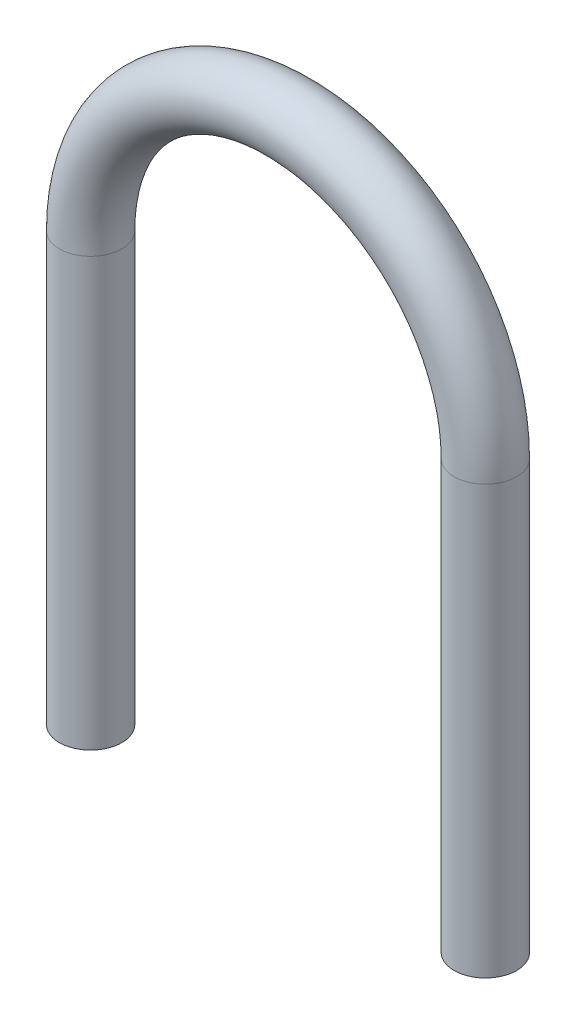
SolidWorks part; units mm, degrees
ref_plane "Front Plane" through (0, 0, 0) normal (0, 0, 1) x (1, 0, 0)
ref_plane "Top Plane" through (0, 0, 0) normal (0, 1, 0) x (1, 0, 0)
ref_plane "Right Plane" through (0, 0, 0) normal (1, 0, 0) x (0, 0, -1)
sketch "Sketch1" plane through (0, 0, 0) normal (0, 0, 1) x (1, 0, 0)
  line L0 (2, 0) -> (2, 12) construction
  line L1 (16, 0) -> (16, 12) construction
  line L2 (0, -7.5) -> (0, 12)
  line L3 (34, 0) -> (34, 12) construction
  line L4 (20, 0) -> (20, 12) construction
  line L5 (52, 0) -> (52, 12) construction
  line L6 (38, 0) -> (38, 12) construction
  line L7 (18, 12) -> (18, -7.5)
  arc A0 (2, 12) -> (16, 12) centre (9, 12) cw construction
  arc A1 (2, 0) -> (16, 0) centre (9, 0) ccw construction
  arc A2 (20, 0) -> (34, 0) centre (27, 0) ccw construction
  arc A3 (20, 12) -> (34, 12) centre (27, 12) cw construction
  arc A4 (38, 0) -> (52, 0) centre (45, 0) ccw construction
  arc A5 (38, 12) -> (52, 12) centre (45, 12) cw construction
  arc A6 (0, 12) -> (18, 12) centre (9, 12) cw
  point P22 (0, 0)
  dimension "D1" = 12
  dimension "D2" = 14
  dimension "D3" = 9
  dimension "D5" = 9
  dimension "D6" = 19.5
  dimension "D4" = 3
ref_plane "Plane2" through (0, -7.5, 0) normal (0, 1, 0) x (1, 0, 0)
sketch "Sketch2" plane through (0, -7.5, 0) normal (0, 1, 0) x (1, 0, 0)
  circle A0 centre (0, 0) radius 1.425
  dimension "D1" = 2.85
sweep "Sweep1" add profiles "Sketch2" path "Sketch1"
